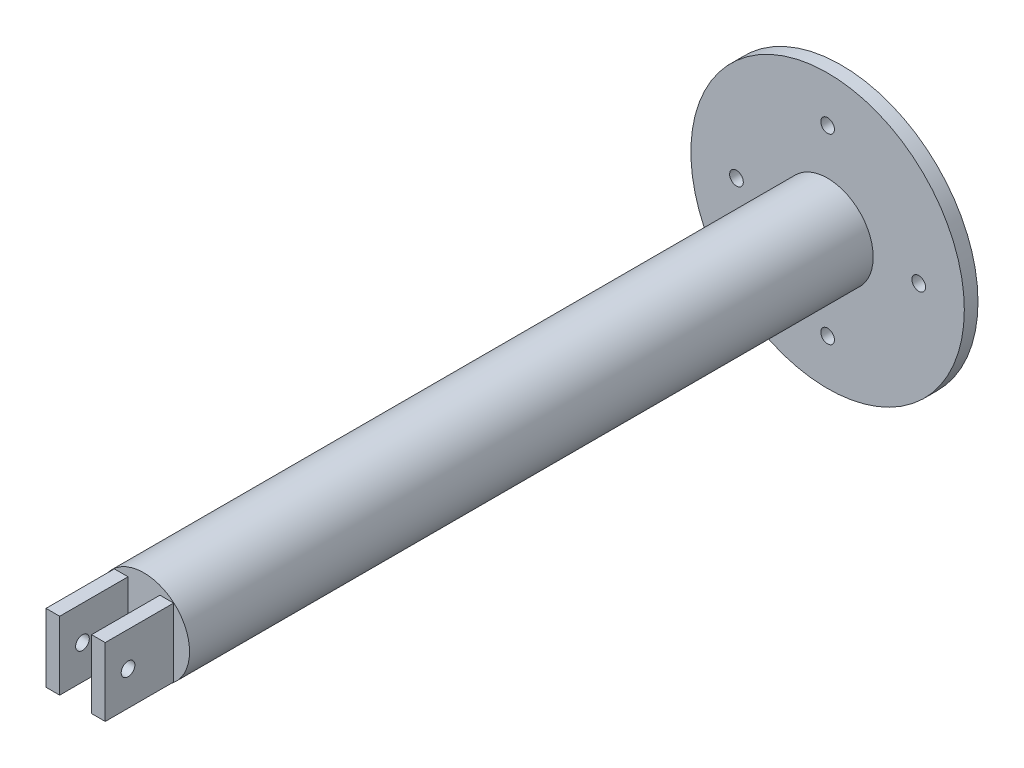
SolidWorks part; units mm, degrees
ref_plane "Спереди" through (0, 0, 0) normal (0, 0, 1) x (1, 0, 0)
ref_plane "Сверху" through (0, 0, 0) normal (0, 1, 0) x (1, 0, 0)
ref_plane "Справа" through (0, 0, 0) normal (1, 0, 0) x (0, 0, -1)
sketch "Эскиз1" plane through (0, 0, 0) normal (0, 0, 1) x (1, 0, 0)
  line L0 (0, 0) -> (-20, 0) construction
  line L1 (0, 0) -> (20, 0) construction
  line L2 (0, 0) -> (0, -20) construction
  line L3 (0, 0) -> (0, 20) construction
  circle A0 centre (0, 0) radius 30
  circle A2 centre (-20, 0) radius 1.5
  circle A3 centre (0, -20) radius 1.5
  circle A4 centre (20, 0) radius 1.5
  circle A5 centre (0, 20) radius 1.5
  point P9 (0, 0)
  dimension "D2" = 60
  dimension "D3" = 3
  dimension "D4" = 20
  dimension "D5" = 20
extrude "Бобышка-Вытянуть1" add sketch "Эскиз1" along normal blind 3
sketch "Эскиз3" plane through (0, 0, 3) normal (0, 0, 1) x (1, 0, 0)
  circle A0 centre (0, 0) radius 10
  dimension "D1" = 20
extrude "Бобышка-Вытянуть3" add sketch "Эскиз3" along normal blind 150
sketch "Эскиз4" plane through (0, 0, 153) normal (0, 0, 1) x (1, 0, 0)
  line L0 (0, 0) -> (0, 10) construction
  line L1 (0, 0) -> (0, -10) construction
  line L2 (0, 0) -> (-10, 0) construction
  line L3 (0, 0) -> (10, 0) construction
  line L5 (-6.5, -7.5) -> (-3.5, -7.5)
  line L6 (-6.5, -7.5) -> (-6.5, 7.5)
  line L7 (-6.5, 7.5) -> (-3.5, 7.5)
  line L8 (-3.5, -7.5) -> (-3.5, 7.5)
  line L9 (-6.5, -7.5) -> (-3.5, 7.5) construction
  line L10 (-6.5, 7.5) -> (-3.5, -7.5) construction
  line L11 (6.5, -7.5) -> (3.5, -7.5)
  line L12 (6.5, -7.5) -> (6.5, 7.5)
  line L13 (6.5, 7.5) -> (3.5, 7.5)
  line L14 (3.5, -7.5) -> (3.5, 7.5)
  line L15 (6.5, -7.5) -> (3.5, 7.5) construction
  line L16 (6.5, 7.5) -> (3.5, -7.5) construction
  circle A0 centre (0, 0) radius 10 construction
  circle A1 centre (0, 0) radius 10 construction
  point P5 (-5, 0)
  point P16 (5, 0)
  dimension "D1" = 15
  dimension "D2" = 3
extrude "Бобышка-Вытянуть4" add sketch "Эскиз4" along normal blind 15
sketch "Эскиз5" plane through (6.5, 0, 0) normal (1, 0, 0) x (0, 0, -1)
  line L0 (-168, -7.5) -> (-168, 7.5) construction
  line L1 (-163, 0) -> (-168, 0) construction
  circle A0 centre (-163, 0) radius 1.5
  dimension "D1" = 3
  dimension "D2" = 5
extrude "Вырез-Вытянуть1" cut sketch "Эскиз5" along direction (1, 0, 0) on the side against the normal through all
